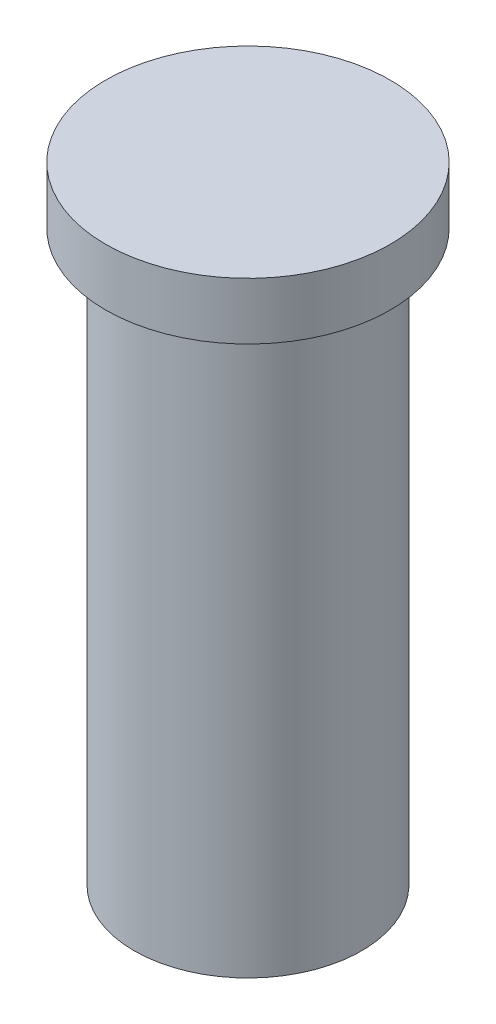
SolidWorks part; units mm, degrees
ref_plane "Front Plane" through (0, 0, 0) normal (0, 0, 1) x (1, 0, 0)
ref_plane "Top Plane" through (0, 0, 0) normal (0, 1, 0) x (1, 0, 0)
ref_plane "Right Plane" through (0, 0, 0) normal (1, 0, 0) x (0, 0, -1)
sketch "Sketch1" plane through (0, 0, 0) normal (0, 1, 0) x (1, 0, 0)
  circle A0 centre (0, 0) radius 12.5
  dimension "D1" = 25
extrude "Boss-Extrude1" add sketch "Sketch1" along normal blind 5
sketch "Sketch2" plane through (0, 0, 0) normal (0, -1, 0) x (1, 0, 0)
  circle A0 centre (0, 0) radius 10
  dimension "D1" = 20
extrude "Boss-Extrude2" add sketch "Sketch2" along normal blind 50
sketch "Sketch3" plane through (0, -50, 0) normal (0, -1, 0) x (1, 0, 0)
  circle A0 centre (0, 0) radius 7.5
  dimension "D1" = 15
extrude "Cut-Extrude1" cut sketch "Sketch3" against normal blind 50
